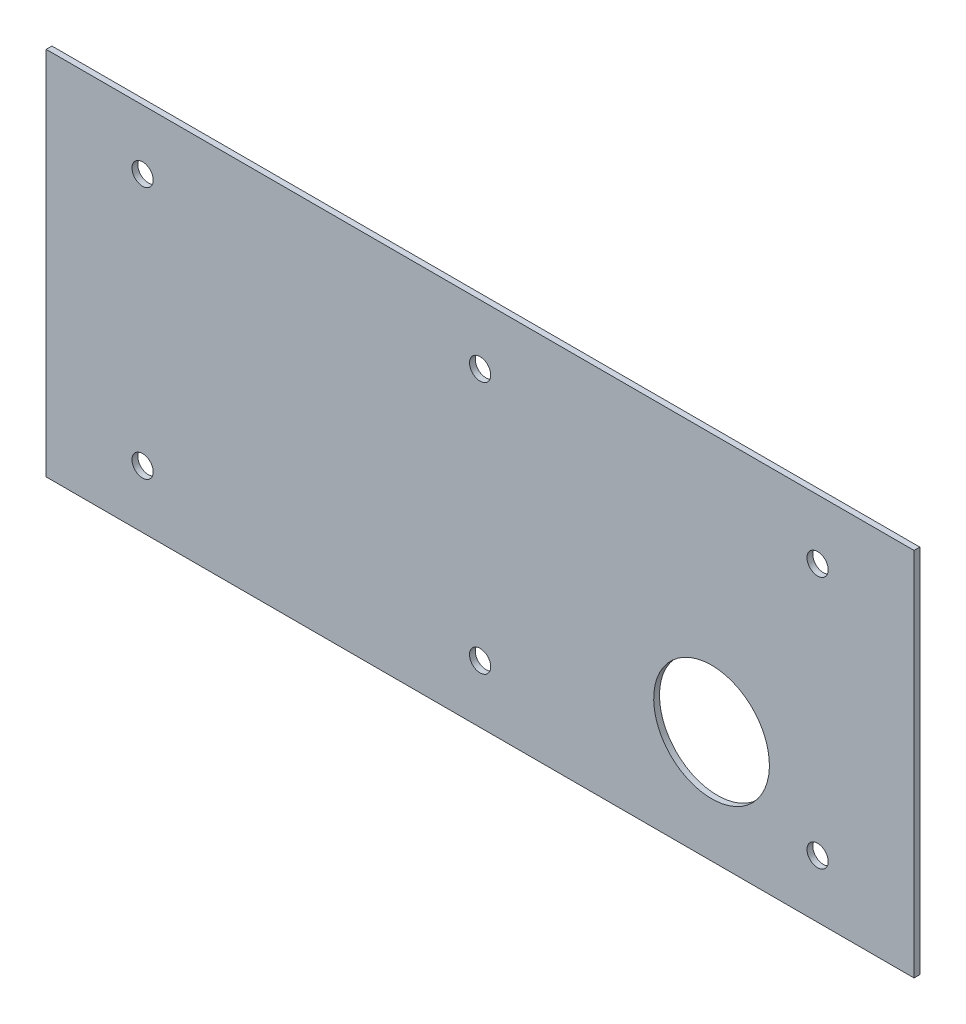
SolidWorks part; units mm, degrees
material "1.0490 (S275N)"
ref_plane "Front Plane" through (0, 0, 0) normal (0, 0, 1) x (1, 0, 0)
ref_plane "Top Plane" through (0, 0, 0) normal (0, 1, 0) x (1, 0, 0)
ref_plane "Right Plane" through (0, 0, 0) normal (1, 0, 0) x (0, 0, -1)
sketch "Sketch1" plane through (0, 0, 0) normal (0, 0, 1) x (1, 0, 0)
  line L0 (-64.1196, 132.7379) -> (-64.1196, -59.2621)
  line L1 (-64.1196, 132.7379) -> (385.8804, 132.7379)
  line L2 (385.8804, 132.7379) -> (385.8804, -59.2621)
  line L3 (385.8804, -59.2621) -> (-64.1196, -59.2621)
extrude "Boss-Extrude1" add sketch "Sketch1" along normal blind 3
extrude "Cut-Extrude1" cut sketch "Sketch2" against normal through all
sketch "Sketch2" plane through (-44.5749, -288.5648, -49) normal (0, 0, -1) x (-1, 0, 0)
  circle A0 centre (-325.4553, 287.2982) radius 30
hole_wizard "M10 Clearance Slot1" positions "Sketch3" profile "Sketch4" size "M10" standard "ISO" slot yes end condition through all
sketch "Sketch3" plane through (-44.5749, -288.5648, -49) normal (0, 0, -1) x (-1, 0, 0)
  point P0 (-380.4553, 390.2982)
  point P2 (-205.4553, 390.2982)
  point P4 (-30.4553, 390.2982)
  point P6 (-30.4553, 259.2982)
  point P8 (-205.4553, 259.2982)
  point P10 (-380.4553, 259.2982)
sketch "Sketch4" plane through (335.8804, 101.7334, -49) normal (1, 0, 0) x (0, 1, 0)
  line L0 (0, 0) -> (0, 52)
  line L1 (0, 52) -> (5.5, 52)
  line L2 (5.5, 52) -> (5.5, 0)
  line L3 (5.5, 0) -> (0, 0)
  line L4 (0, -6.35) -> (0, 107.95) construction
  dimension "Thru Hole Dia." = 11
  dimension "Thru Hole Depth" = 52
